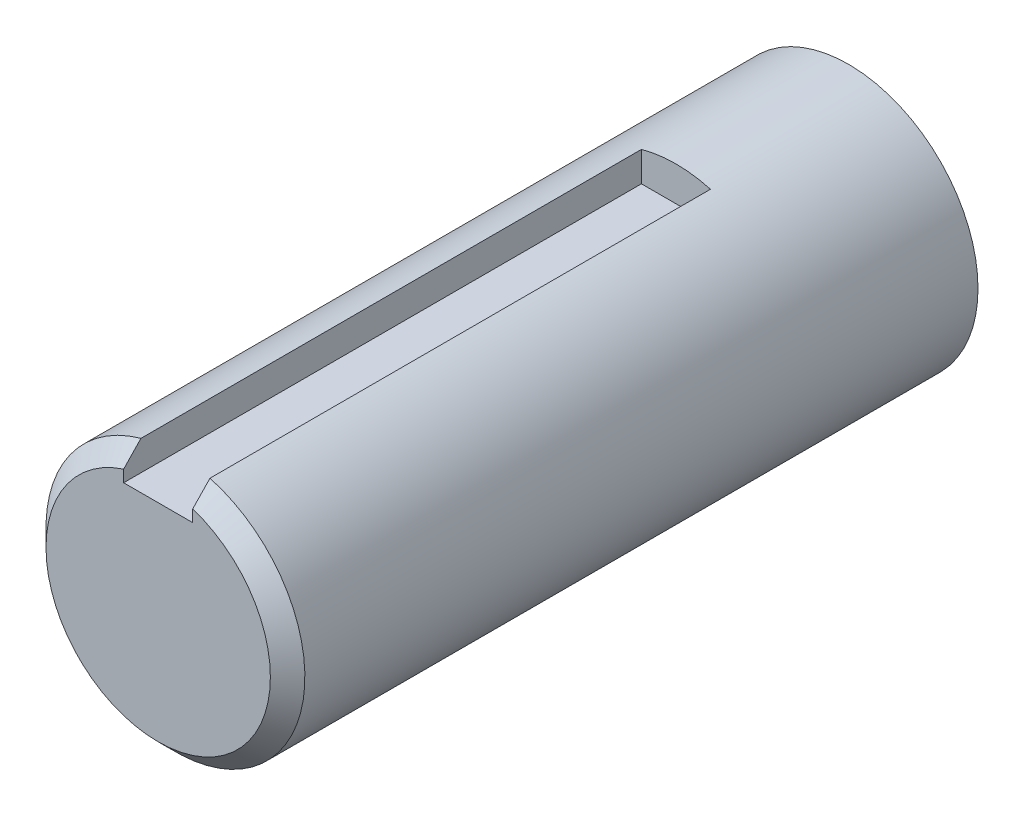
SolidWorks part; units mm, degrees
ref_plane "Front Plane" through (0, 0, 0) normal (0, 0, 1) x (1, 0, 0)
ref_plane "Top Plane" through (0, 0, 0) normal (0, 1, 0) x (1, 0, 0)
ref_plane "Right Plane" through (0, 0, 0) normal (1, 0, 0) x (0, 0, -1)
sketch "Sketch1" plane through (0, 0, 0) normal (0, 0, 1) x (1, 0, 0)
  circle A0 centre (0, 0) radius 15
  dimension "D1" = 30
extrude "Boss-Extrude1" add sketch "Sketch1" along normal mid plane 80
sketch "Sketch2" plane through (0, 0, 40) normal (0, 0, 1) x (1, 0, 0)
  line L0 (0, 0) -> (0, 16.3071) construction
  line L1 (-4, 14.4568) -> (-4, 11)
  line L2 (-4, 11) -> (4, 11)
  line L3 (4, 11) -> (4, 14.4568)
  circle A0 centre (0, 0) radius 15 construction
  circle A2 centre (0, 0) radius 15
  arc A3 (4, 14.4568) -> (-4, 14.4568) centre (0, 0) ccw
  point P10 (0, 15)
  dimension "D1" = 8
  dimension "D2" = 4
  dimension "D3" = 4
  dimension "D4" = 0
extrude "Cut-Extrude1" cut sketch "Sketch2" against normal blind 60
chamfer "Chamfer1" distance 2 angle 45 1 edges at (0, -15, 40)
